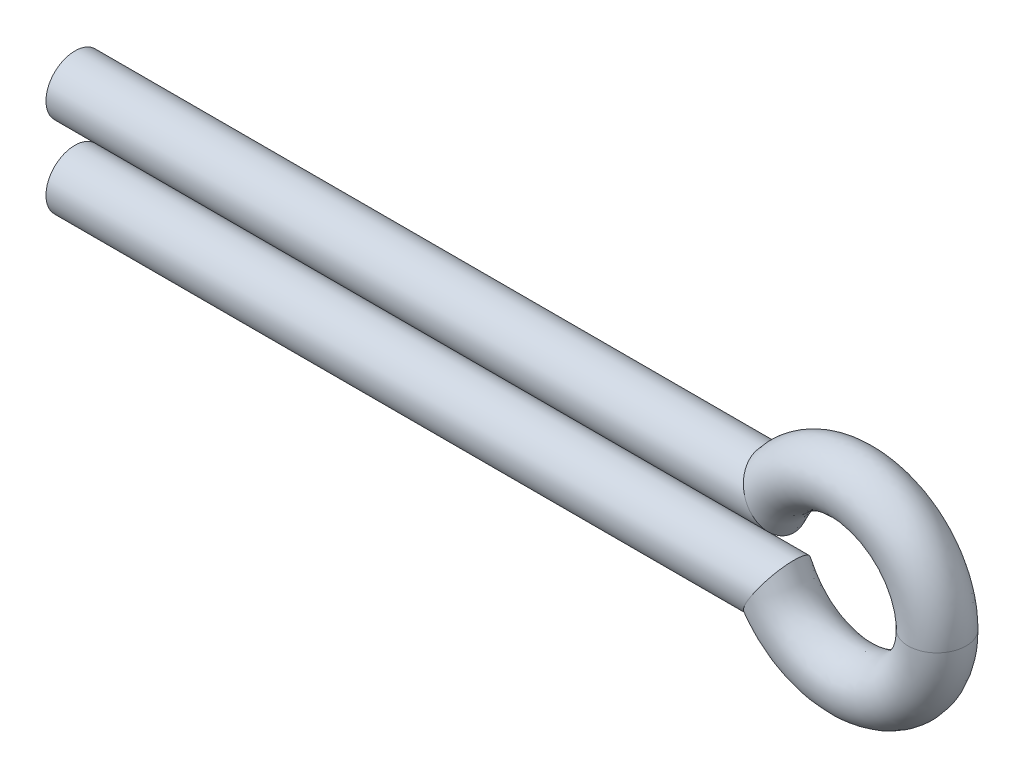
SolidWorks part; units mm, degrees
ref_plane "Front Plane" through (0, 0, 0) normal (0, 0, 1) x (1, 0, 0)
ref_plane "Top Plane" through (0, 0, 0) normal (0, 1, 0) x (1, 0, 0)
ref_plane "Right Plane" through (0, 0, 0) normal (1, 0, 0) x (0, 0, -1)
sketch "Sketch1" plane through (0, 0, 0) normal (0, 0, 1) x (1, 0, 0)
  line L0 (-53.9843, 28.5626) -> (67.3136, 28.5626)
  line L1 (0, -16.2485) -> (0, 16.2485) construction
  line L2 (67.3136, 14.446) -> (-53.9843, 14.446)
  arc A0 (67.3136, 14.446) -> (67.3136, 28.5626) centre (80.2894, 21.5043) ccw
sweep "Sweep2" add path "Sketch1" circular profile diameter 10 parameters "D3"=10
